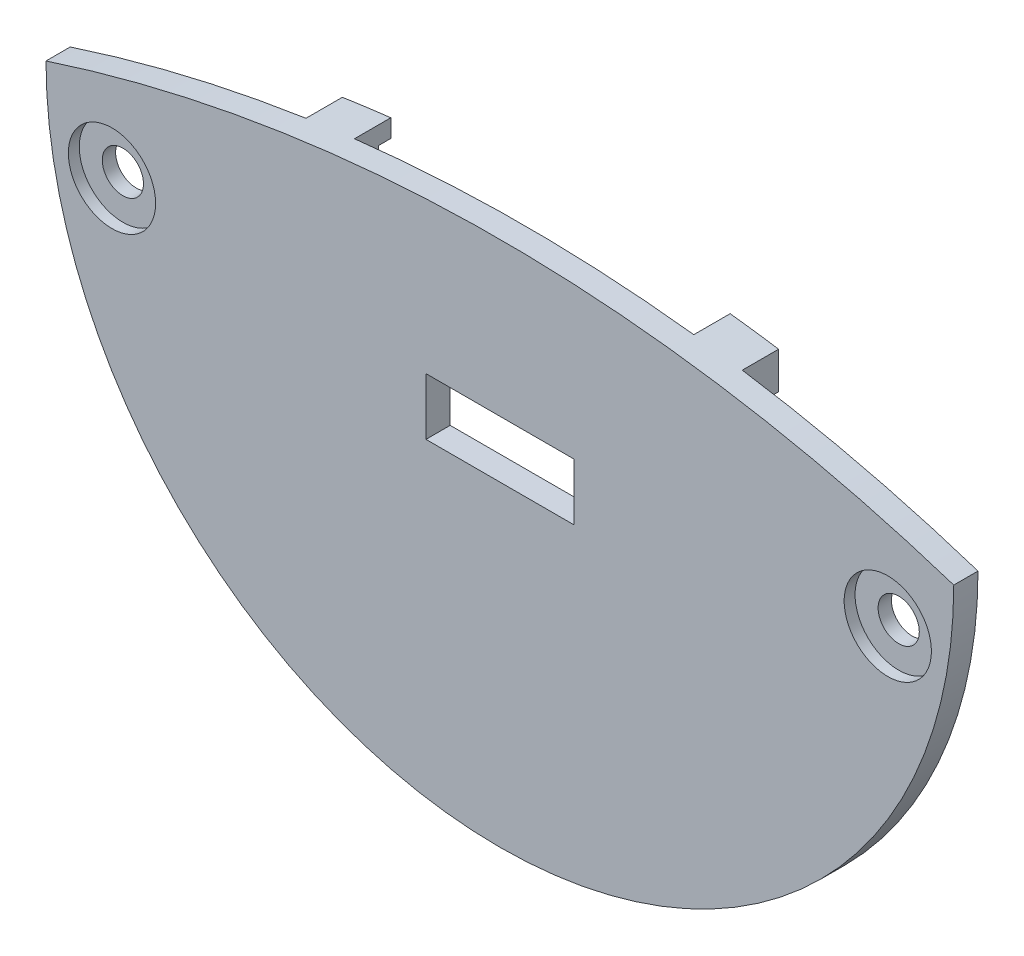
SolidWorks part; units mm, degrees
ref_plane "Front" through (0, 0, 0) normal (0, 0, 1) x (1, 0, 0)
ref_plane "Top" through (0, 0, 0) normal (0, 1, 0) x (1, 0, 0)
ref_plane "Right" through (0, 0, 0) normal (1, 0, 0) x (0, 0, -1)
sketch "草图2" plane through (0, 0, 0) normal (0, 0, 1) x (1, 0, 0)
  line L0 (0, 6) -> (0, -37.45) construction
  line L2 (-6.1, -6.65) -> (6.1, -6.65)
  line L3 (-6.1, -6.65) -> (-6.1, -11.35)
  line L4 (-6.1, -11.35) -> (6.1, -11.35)
  line L5 (6.1, -6.65) -> (6.1, -11.35)
  line L6 (-6.1, -6.65) -> (6.1, -11.35) construction
  line L7 (-6.1, -11.35) -> (6.1, -6.65) construction
  arc A0 (-37.45, 0.0164) -> (37.45, 0.0164) centre (0, 0) ccw construction
  arc A1 (37.45, 0.0164) -> (-37.45, 0.0164) centre (0, -114.1875) ccw construction
  arc A2 (-37.45, 0.0164) -> (37.45, 0.0164) centre (0, 0) ccw
  arc A3 (37.45, 0.0164) -> (-37.45, 0.0164) centre (0, -114.1875) ccw
  circle A4 centre (-32.0063, -5.6436) radius 1.7
  circle A5 centre (32.0063, -5.6436) radius 1.7
  point P12 (0, -9)
  dimension "D1" = 3.4
  dimension "D2" = 3.4
  dimension "D3" = 15
  dimension "D4" = 12.2
  dimension "D5" = 4.7
extrude "凸台-拉伸1" add sketch "草图2" against normal blind 2
sketch "草图3" plane through (0, 0, 0) normal (0, 0, 1) x (1, 0, 0)
  circle A0 centre (-32.0063, -5.6436) radius 3.6
  circle A1 centre (32.0063, -5.6436) radius 3.6
  dimension "D1" = 7.2
  dimension "D2" = 7.2
extrude "切除-拉伸1" cut sketch "草图3" against normal blind 0.9
sketch "草图4" plane through (0, 0, -2) normal (0, 0, -1) x (-1, 0, 0)
  line L0 (-15, -31.65) -> (-15, -33.15) construction
  line L1 (-17, -31.65) -> (-15, -31.65) construction
  line L2 (-17, -33.15) -> (-17, -31.65) construction
  line L3 (-15, -33.15) -> (-17, -33.15) construction
  line L4 (17, -33.15) -> (15, -33.15) construction
  line L5 (17, -31.65) -> (17, -33.15) construction
  line L6 (15, -31.65) -> (17, -31.65) construction
  line L7 (15, -33.15) -> (15, -31.65) construction
  line L8 (-18, 1.6) -> (-18, 4.6445) construction
  line L9 (-14, 1.6) -> (-18, 1.6) construction
  line L10 (-14, 5.1818) -> (-14, 1.6) construction
  line L11 (18, 4.6445) -> (18, 1.6) construction
  line L12 (18, 1.6) -> (14, 1.6) construction
  line L13 (14, 1.6) -> (14, 5.1818) construction
  line L14 (-15, -31.65) -> (-15, -33.15)
  line L15 (-17, -31.65) -> (-15, -31.65)
  line L16 (-17, -33.15) -> (-17, -31.65)
  line L17 (-15, -33.15) -> (-17, -33.15)
  line L18 (17, -33.15) -> (15, -33.15)
  line L19 (17, -31.65) -> (17, -33.15)
  line L20 (15, -31.65) -> (17, -31.65)
  line L21 (15, -33.15) -> (15, -31.65)
  line L22 (-18, 1.6) -> (-18, 4.6445)
  line L23 (-14, 1.6) -> (-18, 1.6)
  line L24 (-14, 5.1818) -> (-14, 1.6)
  line L25 (18, 4.6445) -> (18, 1.6)
  line L26 (18, 1.6) -> (14, 1.6)
  line L27 (14, 1.6) -> (14, 5.1818)
  arc A0 (37.45, 0.0164) -> (-37.45, 0.0164) centre (0, -114.1875) ccw construction
  arc A1 (18, 4.6445) -> (14, 5.1818) centre (0, -114.1875) ccw
  arc A2 (-14, 5.1818) -> (-18, 4.6445) centre (0, -114.1875) ccw
extrude "凸台-拉伸2" add sketch "草图4" along normal blind 2
sketch "草图5" plane through (0, 0, -4) normal (0, 0, -1) x (-1, 0, 0)
  line L0 (-16.1, -32.5) -> (-15, -32.5) construction
  line L1 (-16.1, -31.65) -> (-16.1, -32.5) construction
  line L2 (-17, -31.65) -> (-16.1, -31.65) construction
  line L3 (-17, -33.15) -> (-17, -31.65) construction
  line L4 (-15, -33.15) -> (-17, -33.15) construction
  line L5 (-15, -32.5) -> (-15, -33.15) construction
  line L6 (16.1, -32.5) -> (16.1, -31.65) construction
  line L7 (15, -32.5) -> (16.1, -32.5) construction
  line L8 (15, -33.15) -> (15, -32.5) construction
  line L9 (17, -33.15) -> (15, -33.15) construction
  line L10 (17, -31.65) -> (17, -33.15) construction
  line L11 (16.1, -31.65) -> (17, -31.65) construction
  line L12 (-18, 1.6) -> (-18, 4.6445) construction
  line L13 (-16.1, 1.6) -> (-18, 1.6) construction
  line L14 (-14, 3.7) -> (-16.1, 3.7) construction
  line L15 (-16.1, 3.7) -> (-16.1, 1.6) construction
  line L17 (14, 3.7) -> (14, 5.1818) construction
  line L18 (18, 4.6445) -> (18, 1.6) construction
  line L19 (16.1, 3.7) -> (14, 3.7) construction
  line L20 (16.1, 1.6) -> (16.1, 3.7) construction
  line L21 (18, 1.6) -> (16.1, 1.6) construction
  line L22 (-16.1, -32.5) -> (-15, -32.5)
  line L23 (-16.1, -31.65) -> (-16.1, -32.5)
  line L24 (-17, -31.65) -> (-16.1, -31.65)
  line L25 (-17, -33.15) -> (-17, -31.65)
  line L26 (-15, -33.15) -> (-17, -33.15)
  line L27 (-15, -32.5) -> (-15, -33.15)
  line L28 (16.1, -32.5) -> (16.1, -31.65)
  line L29 (15, -32.5) -> (16.1, -32.5)
  line L30 (15, -33.15) -> (15, -32.5)
  line L31 (17, -33.15) -> (15, -33.15)
  line L32 (17, -31.65) -> (17, -33.15)
  line L33 (16.1, -31.65) -> (17, -31.65)
  line L34 (-18, 1.6) -> (-18, 4.6445)
  line L35 (-16.1, 1.6) -> (-18, 1.6)
  line L36 (-14, 3.7) -> (-16.1, 3.7)
  line L37 (-16.1, 3.7) -> (-16.1, 1.6)
  line L39 (14, 3.7) -> (14, 5.1818)
  line L40 (18, 4.6445) -> (18, 1.6)
  line L41 (16.1, 3.7) -> (14, 3.7)
  line L42 (16.1, 1.6) -> (16.1, 3.7)
  line L43 (18, 1.6) -> (16.1, 1.6)
  line L46 (-14, 3.7) -> (-14, 5.1818)
  arc A0 (37.45, 0.0164) -> (-37.45, 0.0164) centre (0, -114.1875) ccw construction
  arc A3 (18, 4.6445) -> (14, 5.1818) centre (0, -114.1875) ccw
  arc A4 (-14, 5.1818) -> (-18, 4.6445) centre (0, -114.1875) ccw
extrude "凸台-拉伸3" add sketch "草图5" along normal blind 1
